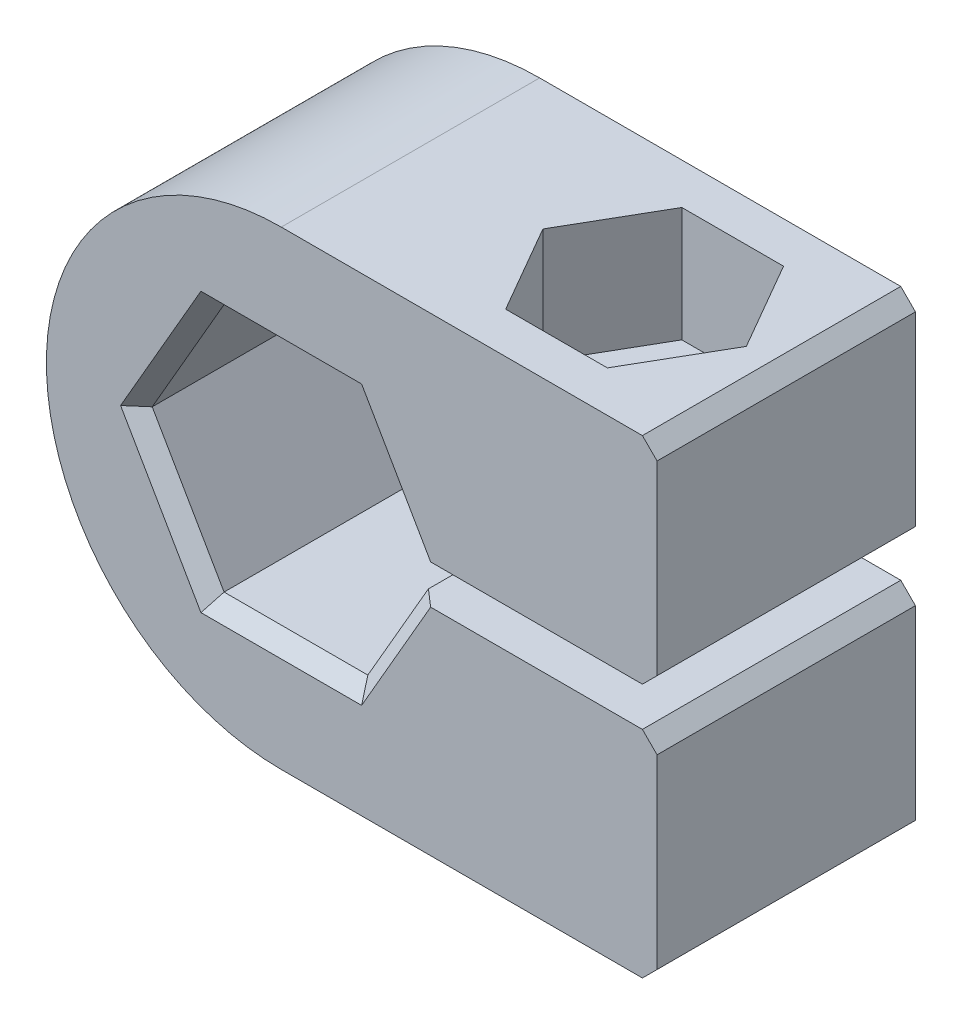
SolidWorks part; units mm, degrees
material "PET"
ref_plane "Front Plane" through (0, 0, 0) normal (0, 0, 1) x (1, 0, 0)
ref_plane "Top Plane" through (0, 0, 0) normal (0, 1, 0) x (1, 0, 0)
ref_plane "Right Plane" through (0, 0, 0) normal (1, 0, 0) x (0, 0, -1)
sketch "Sketch2" plane through (0, 0, 0) normal (0, 0, 1) x (1, 0, 0)
  line L0 (10.16, -12.7) -> (10.16, -1.0583) construction
  line L1 (3.8861, 6.731) -> (-3.8861, 6.731) construction
  line L2 (-3.8861, 6.731) -> (-7.7723, 0) construction
  line L3 (-7.7723, 0) -> (-3.8861, -6.731) construction
  line L4 (-3.8861, -6.731) -> (3.8861, -6.731) construction
  line L5 (3.8861, -6.731) -> (7.7723, 0) construction
  line L6 (7.7723, 0) -> (3.8861, 6.731) construction
  line L8 (3.8861, -6.731) -> (7.1613, -1.0583)
  line L9 (-3.8861, -6.731) -> (3.8861, -6.731)
  line L10 (-7.7723, 0) -> (-3.8861, -6.731)
  line L11 (-3.8861, 6.731) -> (-7.7723, 0)
  line L12 (3.8861, 6.731) -> (-3.8861, 6.731)
  line L13 (7.1613, 1.0583) -> (3.8861, 6.731)
  line L14 (10.16, 1.0583) -> (7.1613, 1.0583)
  line L15 (7.1613, -1.0583) -> (10.16, -1.0583)
  line L32 (10.16, 1.0583) -> (20.32, 1.0583)
  line L34 (20.32, 1.0583) -> (20.32, 12.7)
  line L36 (20.32, 12.7) -> (0, 12.7)
  line L37 (0, -12.7) -> (20.32, -12.7)
  line L39 (20.32, -12.7) -> (20.32, -1.0583)
  line L41 (20.32, -1.0583) -> (10.16, -1.0583)
  line L48 (15.875, 1.0583) -> (8.9943, 1.0583) construction
  line L49 (0, 12.7) -> (15.875, 12.7) construction
  circle A0 centre (0, 0) radius 6.731 construction
  arc A2 (0, 12.7) -> (0, -12.7) centre (0, 0) ccw
  point P46 (-12.7, 0)
  dimension "D2" = 33.02
  dimension "D1" = 13.462
extrude "Boss-Extrude1" add sketch "Sketch2" along normal blind 13.97
chamfer "Chamfer1" distance 0.7937 angle 45 16 edges at (5.5237, -3.8947, 0) (0, -6.731, 0) (-5.8292, -3.3655, 0) (-5.8292, 3.3655, 0) (0, 6.731, 0) (5.5237, 3.8947, 0) (5.5237, 3.8947, 13.97) (0, 6.731, 13.97) (-5.8292, 3.3655, 13.97) (-5.8292, -3.3655, 13.97) (0, -6.731, 13.97) (5.5237, -3.8947, 13.97) (20.32, -12.7, 6.985) (20.32, 12.7, 6.985) (20.32, 1.0583, 6.985) (20.32, -1.0583, 6.985)
sketch "Sketch3" plane through (0, 12.7, 0) normal (0, 1, 0) x (1, 0, 0)
  line L0 (7.1613, -13.1762) -> (7.1613, -0.7938) construction
  line L1 (15.4102, -11.7475) -> (18.1598, -6.985)
  line L2 (20.32, -13.97) -> (20.32, 0) construction
  line L5 (18.1598, -6.985) -> (15.4102, -2.2225)
  line L6 (15.4102, -2.2225) -> (9.9109, -2.2225)
  line L7 (9.9109, -2.2225) -> (7.1613, -6.985)
  line L8 (7.1613, -6.985) -> (9.9109, -11.7475)
  line L9 (9.9109, -11.7475) -> (15.4102, -11.7475)
  circle A0 centre (12.6605, -6.985) radius 2.4892
  circle A1 centre (12.6605, -6.985) radius 4.7625 construction
  point P2 (16.5957, -11.1125)
  point P7 (20.32, -6.985)
  point P13 (7.434, -6.35)
  dimension "D1" = 4.9784
  dimension "D2" = 9.525
extrude "Cut-Extrude1" cut sketch "Sketch3" against normal through all contours A0
sketch "Sketch4" plane through (0, 12.7, 0) normal (0, 1, 0) x (1, 0, 0)
  line L1 (9.9109, -11.7475) -> (15.4102, -11.7475)
  line L2 (15.4102, -11.7475) -> (18.1598, -6.985)
  line L3 (18.1598, -6.985) -> (15.4102, -2.2225)
  line L4 (15.4102, -2.2225) -> (9.9109, -2.2225)
  line L5 (9.9109, -2.2225) -> (7.1613, -6.985)
  line L6 (7.1613, -6.985) -> (9.9109, -11.7475)
  circle A0 centre (12.6605, -6.985) radius 4.7625 construction
  dimension "D1" = 9.525
extrude "Cut-Extrude2" cut sketch "Sketch4" against normal blind 6.2
sketch "Sketch5" plane through (0, -12.7, 0) normal (0, -1, 0) x (1, 0, 0)
  circle A0 centre (12.6605, 6.985) radius 4.064
  dimension "D1" = 8.128
extrude "Cut-Extrude3" cut sketch "Sketch5" against normal blind 6.35
chamfer "Chaflán1" distance 0.7937 angle 45 3 edges at (16.7245, -12.7, 6.985) (15.1497, -1.0583, 6.985) (12.6605, 1.0583, 9.4742)
